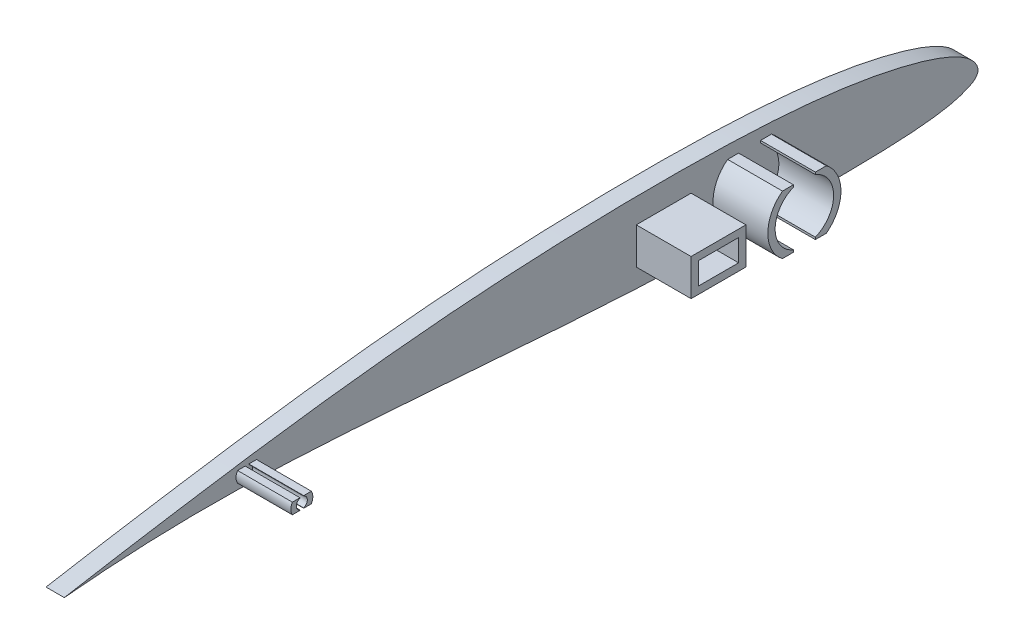
SolidWorks part; units mm, degrees
material "ABS generico"
ref_plane "Piano frontale" through (0, 0, 0) normal (0, 0, 1) x (1, 0, 0)
ref_plane "Piano superiore" through (0, 0, 0) normal (0, 1, 0) x (1, 0, 0)
ref_plane "Piano destro" through (0, 0, 0) normal (1, 0, 0) x (0, 0, -1)
curve "Curva1"
  spline degree 3 poles (0, 0.1724, 248.285) (0, -0.053, 250.4273) (0, 0.2462, 248.3284) (0, 0.5529, 246.6445) (0, 1.2459, 242.6221) (0, 2.0989, 237.7464) (0, 3.1818, 231.3634) (0, 4.2933, 223.9772) (0, 5.7312, 215.5604) (0, 7.1315, 206.3004) (0, 8.6324, 196.1631) (0, 10.1162, 185.3524) (0, 11.5493, 173.9891) (0, 12.8816, 162.1914) (0, 14.0593, 150.0724) (0, 15.0523, 137.7438) (0, 15.8256, 125.3116) (0, 16.3834, 112.8888) (0, 16.7267, 100.597) (0, 16.8648, 88.5669) (0, 16.792, 76.9314) (0, 16.4941, 65.8165) (0, 15.9609, 55.3329) (0, 15.1594, 45.573) (0, 14.0978, 36.6074) (0, 12.7884, 28.4972) (0, 11.2839, 21.2988) (0, 9.6413, 15.0749) (0, 7.9136, 9.8809) (0, 6.1182, 5.7699) (0, 4.2384, 2.7289) (0, 2.3057, 0.8126) (0, 0.7927, 0.0312) (0, -0.4105, -0.0213) (0, -1.7115, 0.4949) (0, -2.8658, 2.6253) (0, -4.0404, 5.6977) (0, -4.9287, 10.0719) (0, -5.5974, 15.6262) (0, -6.0122, 22.4122) (0, -6.265, 30.3619) (0, -6.3814, 39.3972) (0, -6.3554, 49.3987) (0, -6.2185, 60.2453) (0, -5.9476, 71.8018) (0, -5.5368, 83.9408) (0, -4.9386, 96.5461) (0, -4.1527, 109.5201) (0, -3.2196, 122.7671) (0, -2.1909, 136.1764) (0, -1.148, 149.6158) (0, -0.1602, 162.9314) (0, 0.706, 175.9537) (0, 1.3896, 188.4999) (0, 1.8332, 200.3712) (0, 1.9676, 211.3376) (0, 1.8232, 221.1842) (0, 1.4973, 229.6804) (0, 1.0741, 236.8065) (0, 0.6857, 242.1894) (0, 0.3087, 246.5181) (0, 0.1724, 248.285) (0, -0.053, 250.4273) (0, 0.2462, 248.3284) knots -0.014202 -0.006329 -0.001589 0 0.001576 0.006211 0.01368 0.023764 0.036307 0.051658 0.068045 0.086769 0.107053 0.128647 0.151303 0.174786 0.19886 0.223309 0.247929 0.272522 0.296848 0.320648 0.343669 0.365658 0.3864 0.405741 0.423561 0.439779 0.454311 0.467034 0.477831 0.486643 0.493542 0.498786 0.50271 0.50309 0.505896 0.510322 0.516831 0.525521 0.536535 0.549945 0.565696 0.583577 0.603379 0.624844 0.647727 0.671743 0.696673 0.722357 0.748609 0.77521 0.801891 0.828329 0.854175 0.879074 0.902636 0.924421 0.943939 0.960827 0.974827 0.985798 0.993671 0.998411 1 1.001576 1.006211 1.01368 periodic
sketch "Schizzo1" plane through (0, 0, 0) normal (1, 0, 0) x (0, 0, -1)
  line L0 (-250, 0) -> (0.0001, 0.0174) construction
  line L1 (0.0001, 0.0174) -> (-0.0034, 50.0174) construction
  line L2 (-62.4999, 16.3096) -> (-62.4999, -6.155) construction
  line L4 (-78.4999, 10.0773) -> (-93.4999, 10.0773) construction
  line L5 (-78.4999, 10.0773) -> (-78.4999, 0.0773) construction
  line L6 (-78.4999, 0.0773) -> (-93.4999, 0.0773) construction
  line L7 (-93.4999, 10.0773) -> (-93.4999, 0.0773) construction
  circle A0 centre (-62.4999, 5.0773) radius 8 construction
  spline S0 degree 3 poles (-248.3284, 0.2462) (-250.4273, -0.053) (-248.285, 0.1724) (-246.5181, 0.3087) (-242.1894, 0.6857) (-236.8065, 1.0741) (-229.6804, 1.4973) (-221.1842, 1.8232) (-211.3376, 1.9676) (-200.3712, 1.8332) (-188.4999, 1.3896) (-175.9537, 0.706) (-162.9314, -0.1602) (-149.6158, -1.148) (-136.1764, -2.1909) (-122.7671, -3.2196) (-109.5201, -4.1527) (-96.5461, -4.9386) (-83.9408, -5.5368) (-71.8018, -5.9476) (-60.2453, -6.2185) (-49.3987, -6.3554) (-39.3972, -6.3814) (-30.3619, -6.265) (-22.4122, -6.0122) (-15.6262, -5.5974) (-10.0719, -4.9287) (-5.6977, -4.0404) (-2.6253, -2.8658) (-0.4949, -1.7115) (0.0213, -0.4105) (-0.0312, 0.7927) (-0.8126, 2.3057) (-2.7289, 4.2384) (-5.7699, 6.1182) (-9.8809, 7.9136) (-15.0749, 9.6413) (-21.2988, 11.2839) (-28.4972, 12.7884) (-36.6074, 14.0978) (-45.573, 15.1594) (-55.3329, 15.9609) (-65.8165, 16.4941) (-76.9314, 16.792) (-88.5669, 16.8648) (-100.597, 16.7267) (-112.8888, 16.3834) (-125.3116, 15.8256) (-137.7438, 15.0523) (-150.0724, 14.0593) (-162.1914, 12.8816) (-173.9891, 11.5493) (-185.3524, 10.1162) (-196.1631, 8.6324) (-206.3004, 7.1315) (-215.5604, 5.7312) (-223.9772, 4.2933) (-231.3634, 3.1818) (-237.7464, 2.0989) (-242.6221, 1.2459) (-246.6445, 0.5529) (-248.3284, 0.2462) (-250.4273, -0.053) (-248.285, 0.1724) knots -0.01368 -0.006211 -0.001576 0 0.001589 0.006329 0.014202 0.025173 0.039173 0.056061 0.075579 0.097364 0.120926 0.145825 0.171671 0.198109 0.22479 0.251391 0.277643 0.303327 0.328257 0.352273 0.375156 0.396621 0.416423 0.434304 0.450055 0.463465 0.474479 0.483169 0.489678 0.494104 0.49691 0.49729 0.501214 0.506458 0.513357 0.522169 0.532966 0.545689 0.560221 0.576439 0.594259 0.6136 0.634342 0.656331 0.679352 0.703152 0.727478 0.752071 0.776691 0.80114 0.825214 0.848697 0.871353 0.892947 0.913231 0.931955 0.948342 0.963693 0.976236 0.98632 0.993789 0.998424 1 1.001589 1.006329 1.014202 only from (-250, 0) to (-250, 0) construction
  spline S1 degree 3 poles (-248.3284, 0.2462) (-250.4273, -0.053) (-248.285, 0.1724) (-246.5181, 0.3087) (-242.1894, 0.6857) (-236.8065, 1.0741) (-229.6804, 1.4973) (-221.1842, 1.8232) (-211.3376, 1.9676) (-200.3712, 1.8332) (-188.4999, 1.3896) (-175.9537, 0.706) (-162.9314, -0.1602) (-149.6158, -1.148) (-136.1764, -2.1909) (-122.7671, -3.2196) (-109.5201, -4.1527) (-96.5461, -4.9386) (-83.9408, -5.5368) (-71.8018, -5.9476) (-60.2453, -6.2185) (-49.3987, -6.3554) (-39.3972, -6.3814) (-30.3619, -6.265) (-22.4122, -6.0122) (-15.6262, -5.5974) (-10.0719, -4.9287) (-5.6977, -4.0404) (-2.6253, -2.8658) (-0.4949, -1.7115) (0.0213, -0.4105) (-0.0312, 0.7927) (-0.8126, 2.3057) (-2.7289, 4.2384) (-5.7699, 6.1182) (-9.8809, 7.9136) (-15.0749, 9.6413) (-21.2988, 11.2839) (-28.4972, 12.7884) (-36.6074, 14.0978) (-45.573, 15.1594) (-55.3329, 15.9609) (-65.8165, 16.4941) (-76.9314, 16.792) (-88.5669, 16.8648) (-100.597, 16.7267) (-112.8888, 16.3834) (-125.3116, 15.8256) (-137.7438, 15.0523) (-150.0724, 14.0593) (-162.1914, 12.8816) (-173.9891, 11.5493) (-185.3524, 10.1162) (-196.1631, 8.6324) (-206.3004, 7.1315) (-215.5604, 5.7312) (-223.9772, 4.2933) (-231.3634, 3.1818) (-237.7464, 2.0989) (-242.6221, 1.2459) (-246.6445, 0.5529) (-248.3284, 0.2462) (-250.4273, -0.053) (-248.285, 0.1724) knots -0.01368 -0.006211 -0.001576 0 0.001589 0.006329 0.014202 0.025173 0.039173 0.056061 0.075579 0.097364 0.120926 0.145825 0.171671 0.198109 0.22479 0.251391 0.277643 0.303327 0.328257 0.352273 0.375156 0.396621 0.416423 0.434304 0.450055 0.463465 0.474479 0.483169 0.489678 0.494104 0.49691 0.49729 0.501214 0.506458 0.513357 0.522169 0.532966 0.545689 0.560221 0.576439 0.594259 0.6136 0.634342 0.656331 0.679352 0.703152 0.727478 0.752071 0.776691 0.80114 0.825214 0.848697 0.871353 0.892947 0.913231 0.931955 0.948342 0.963693 0.976236 0.98632 0.993789 0.998424 1 1.001589 1.006329 1.014202 only from (-250, 0) to (-250, 0)
  point P11 (-78.4999, 5.0773)
  dimension "D3" = 16
  dimension "D1" = 50
  dimension "D2" = 62.5
  dimension "D4" = 15
  dimension "D5" = 10
  dimension "D6" = 16
extrude "CorpoFoam" add sketch "Schizzo1" along normal blind 5
sketch "Schizzo3" plane through (5, 0, 0) normal (1, 0, 0) x (0, 0, -1)
  line L0 (-200, 8.0593) -> (-200, 1.7757) construction
  line L1 (-200.5, 6.4175) -> (-199.5, 3.4175) construction
  line L2 (-197.4019, 6.4175) -> (-199.5, 6.4175)
  line L4 (-197.4019, 3.4175) -> (-199.5, 3.4175)
  line L7 (-200.5, 6.4175) -> (-200.5, 6.3317)
  line L9 (-199.5, 6.4175) -> (-199.5, 6.3317)
  line L10 (-199.5, 6.4175) -> (-200.5, 3.4175) construction
  line L11 (-200.5, 6.4175) -> (-202.5981, 6.4175)
  line L12 (-200.5, 3.4175) -> (-202.5981, 3.4175)
  line L13 (-199.5, 3.5033) -> (-199.5, 3.4175)
  line L14 (-200.5, 3.5033) -> (-200.5, 3.4175)
  arc A0 (-200.5, 6.3317) -> (-200.5, 3.5033) centre (-200, 4.9175) ccw
  arc A1 (-202.5981, 6.4175) -> (-202.5981, 3.4175) centre (-200, 4.9175) ccw
  arc A2 (-197.4019, 3.4175) -> (-197.4019, 6.4175) centre (-200, 4.9175) ccw
  arc A3 (-199.5, 3.5033) -> (-199.5, 6.3317) centre (-200, 4.9175) ccw
  spline S0 degree 3 poles (-248.3284, 0.2462) (-250.4273, -0.053) (-248.285, 0.1724) (-246.5181, 0.3087) (-242.1894, 0.6857) (-236.8065, 1.0741) (-229.6804, 1.4973) (-221.1842, 1.8232) (-211.3376, 1.9676) (-200.3712, 1.8332) (-188.4999, 1.3896) (-175.9537, 0.706) (-162.9314, -0.1602) (-149.6158, -1.148) (-136.1764, -2.1909) (-122.7671, -3.2196) (-109.5201, -4.1527) (-96.5461, -4.9386) (-83.9408, -5.5368) (-71.8018, -5.9476) (-60.2453, -6.2185) (-49.3987, -6.3554) (-39.3972, -6.3814) (-30.3619, -6.265) (-22.4122, -6.0122) (-15.6262, -5.5974) (-10.0719, -4.9287) (-5.6977, -4.0404) (-2.6253, -2.8658) (-0.4949, -1.7115) (0.0213, -0.4105) (-0.0312, 0.7927) (-0.8126, 2.3057) (-2.7289, 4.2384) (-5.7699, 6.1182) (-9.8809, 7.9136) (-15.0749, 9.6413) (-21.2988, 11.2839) (-28.4972, 12.7884) (-36.6074, 14.0978) (-45.573, 15.1594) (-55.3329, 15.9609) (-65.8165, 16.4941) (-76.9314, 16.792) (-88.5669, 16.8648) (-100.597, 16.7267) (-112.8888, 16.3834) (-125.3116, 15.8256) (-137.7438, 15.0523) (-150.0724, 14.0593) (-162.1914, 12.8816) (-173.9891, 11.5493) (-185.3524, 10.1162) (-196.1631, 8.6324) (-206.3004, 7.1315) (-215.5604, 5.7312) (-223.9772, 4.2933) (-231.3634, 3.1818) (-237.7464, 2.0989) (-242.6221, 1.2459) (-246.6445, 0.5529) (-248.3284, 0.2462) (-250.4273, -0.053) (-248.285, 0.1724) knots -0.01368 -0.006211 -0.001576 0 0.001589 0.006329 0.014202 0.025173 0.039173 0.056061 0.075579 0.097364 0.120926 0.145825 0.171671 0.198109 0.22479 0.251391 0.277643 0.303327 0.328257 0.352273 0.375156 0.396621 0.416423 0.434304 0.450055 0.463465 0.474479 0.483169 0.489678 0.494104 0.49691 0.49729 0.501214 0.506458 0.513357 0.522169 0.532966 0.545689 0.560221 0.576439 0.594259 0.6136 0.634342 0.656331 0.679352 0.703152 0.727478 0.752071 0.776691 0.80114 0.825214 0.848697 0.871353 0.892947 0.913231 0.931955 0.948342 0.963693 0.976236 0.98632 0.993789 0.998424 1 1.001589 1.006329 1.014202 only from (-250, 0) to (-250, 0) construction
  dimension "D1" = 3
  dimension "D2" = 6
  dimension "D3" = 50
  dimension "D4" = 1
extrude "PernoAggancioAlettone" add sketch "Schizzo3" along normal blind 15
sketch "Schizzo4" plane through (0, 0, 0) normal (-1, 0, 0) x (0, 0, 1)
  line L0 (80.4999, 8.0773) -> (80.4999, 2.0773)
  line L1 (56.4999, 13.0773) -> (59.4999, 13.0773)
  line L3 (56.4999, -2.9227) -> (59.4999, -2.9227)
  line L5 (78.4999, 10.0773) -> (93.4999, 10.0773)
  line L6 (78.4999, 10.0773) -> (78.4999, 0.0773)
  line L7 (78.4999, 0.0773) -> (93.4999, 0.0773)
  line L8 (93.4999, 10.0773) -> (93.4999, 0.0773)
  line L9 (80.4999, 2.0773) -> (91.4999, 2.0773)
  line L10 (91.4999, 8.0773) -> (91.4999, 2.0773)
  line L11 (80.4999, 8.0773) -> (91.4999, 8.0773)
  line L12 (59.4999, 13.0773) -> (65.4999, -2.9227) construction
  line L14 (59.4999, 13.0773) -> (59.4999, 12.4935)
  line L16 (65.4999, 13.0773) -> (65.4999, 12.4935)
  line L17 (65.4999, 13.0773) -> (68.4999, 13.0773)
  line L18 (65.4999, -2.3389) -> (65.4999, -2.9227)
  line L19 (59.4999, -2.3389) -> (59.4999, -2.9227)
  line L20 (65.4999, -2.9227) -> (68.4999, -2.9227)
  arc A0 (59.4999, 12.4935) -> (59.4999, -2.3389) centre (62.4999, 5.0773) ccw
  arc A1 (56.4999, 13.0773) -> (56.4999, -2.9227) centre (62.4999, 5.0773) ccw
  arc A3 (68.4999, -2.9227) -> (68.4999, 13.0773) centre (62.4999, 5.0773) ccw
  arc A4 (65.4999, -2.3389) -> (65.4999, 12.4935) centre (62.4999, 5.0773) ccw
  dimension "D1" = 20
  dimension "D2" = 2
  dimension "D3" = 6
  dimension "D4" = 3
extrude "Estrusione-Estrusione1" add sketch "Schizzo4" against normal blind 20
